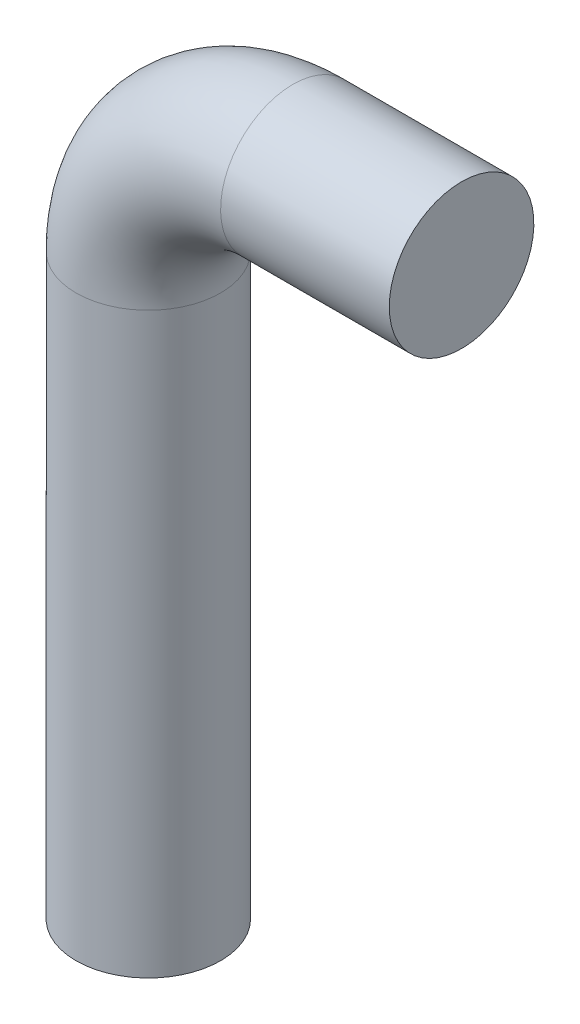
SolidWorks part; units mm, degrees
material "Plain Carbon Steel"
ref_plane "Front Plane" through (0, 0, 0) normal (0, 0, 1) x (1, 0, 0)
ref_plane "Top Plane" through (0, 0, 0) normal (0, 1, 0) x (1, 0, 0)
ref_plane "Right Plane" through (0, 0, 0) normal (1, 0, 0) x (0, 0, -1)
sketch "Sketch1" plane through (0, 0, 0) normal (0, 0, 1) x (1, 0, 0)
  line L0 (0, 0) -> (0, 12)
  line L1 (3, 15) -> (6.5, 15)
  arc A0 (3, 15) -> (0, 12) centre (3, 12) ccw
  dimension "D1" = 12
  dimension "D2" = 3
  dimension "D3" = 12
  dimension "D4" = 3.5
sketch "Sketch2" plane through (0, 0, 0) normal (0, 1, 0) x (1, 0, 0)
  circle A0 centre (0, 0) radius 1.5
  dimension "D1" = 3
sweep "Sweep1" add profiles "Sketch2" path "Sketch1"
